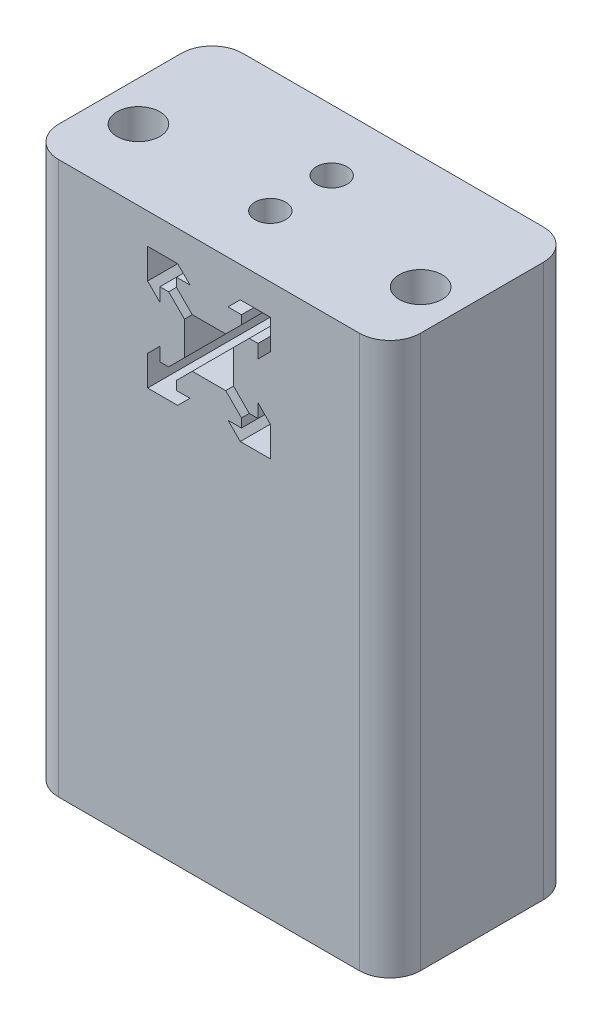
SolidWorks part; units mm, degrees
ref_plane "Front Plane" through (0, 0, 0) normal (0, 0, 1) x (1, 0, 0)
ref_plane "Top Plane" through (0, 0, 0) normal (0, 1, 0) x (1, 0, 0)
ref_plane "Right Plane" through (0, 0, 0) normal (1, 0, 0) x (0, 0, -1)
sketch "Sketch1" plane through (0, 0, 0) normal (0, 0, 1) x (1, 0, 0)
  line L1 (-29.5, 15) -> (29.5, 15)
  line L2 (-29.5, 15) -> (-29.5, -15)
  line L3 (-29.5, -15) -> (29.5, -15)
  line L4 (29.5, 15) -> (29.5, -15)
  line L5 (-29.5, 15) -> (29.5, -15) construction
  line L6 (-29.5, -15) -> (29.5, 15) construction
  line L90 (4, 2.7272) -> (6.5728, 5.3)
  line L91 (6.5728, 5.3) -> (8, 5.3)
  line L92 (8, 5.3) -> (8, 3.1)
  line L93 (8, 3.1) -> (10, 5.1)
  line L94 (10, 5.1) -> (10, 10)
  line L95 (10, 10) -> (5.1, 10)
  line L96 (5.1, 10) -> (3.1, 8)
  line L97 (3.1, 8) -> (5.3, 8)
  line L98 (5.3, 8) -> (5.3, 6.5728)
  line L99 (5.3, 6.5728) -> (2.7272, 4)
  line L100 (2.7272, 4) -> (-2.7272, 4)
  line L101 (-2.7272, 4) -> (-5.3, 6.5728)
  line L102 (-5.3, 6.5728) -> (-5.3, 8)
  line L103 (-5.3, 8) -> (-3.1, 8)
  line L104 (-3.1, 8) -> (-5.1, 10)
  line L105 (-5.1, 10) -> (-10, 10)
  line L106 (-10, 10) -> (-10, 5.1)
  line L107 (-10, 5.1) -> (-8, 3.1)
  line L108 (-8, 3.1) -> (-8, 5.3)
  line L109 (-8, 5.3) -> (-6.5728, 5.3)
  line L110 (-6.5728, 5.3) -> (-4, 2.7272)
  line L111 (-4, 2.7272) -> (-4, -2.7272)
  line L112 (-4, -2.7272) -> (-6.5728, -5.3)
  line L113 (-6.5728, -5.3) -> (-8, -5.3)
  line L114 (-8, -5.3) -> (-8, -3.1)
  line L115 (-8, -3.1) -> (-10, -5.1)
  line L116 (-10, -5.1) -> (-10, -10)
  line L117 (-10, -10) -> (-5.1, -10)
  line L118 (-5.1, -10) -> (-3.1, -8)
  line L119 (-3.1, -8) -> (-5.3, -8)
  line L120 (-5.3, -8) -> (-5.3, -6.5728)
  line L121 (-5.3, -6.5728) -> (-2.7272, -4)
  line L122 (-2.7272, -4) -> (2.7272, -4)
  line L123 (2.7272, -4) -> (5.3, -6.5728)
  line L124 (5.3, -6.5728) -> (5.3, -8)
  line L125 (5.3, -8) -> (3.1, -8)
  line L126 (3.1, -8) -> (5.1, -10)
  line L127 (5.1, -10) -> (10, -10)
  line L128 (10, -10) -> (10, -5.1)
  line L129 (10, -5.1) -> (8, -3.1)
  line L130 (8, -3.1) -> (8, -5.3)
  line L131 (8, -5.3) -> (6.5728, -5.3)
  line L132 (6.5728, -5.3) -> (4, -2.7272)
  line L133 (4, -2.7272) -> (4, 2.7272)
  point P2 (0, 0)
  dimension "D1" = 20
  dimension "D2" = 59
  dimension "D3" = 30
extrude "Boss-Extrude1" add sketch "Sketch1" against normal blind 30
sketch "Sketch2" plane through (0, 15, 0) normal (0, 1, 0) x (1, 0, 0)
  circle A0 centre (0, 10) radius 2.5
  circle A1 centre (0, 20) radius 2.5
  circle A7 centre (23, 11.5) radius 3.5
  circle A9 centre (-23, 11.5) radius 3.5
  dimension "D1" = 10
  dimension "D2" = 10
extrude "Cut-Extrude1" cut sketch "Sketch2" against normal through all
sketch "Sketch3" plane through (0, 0, 0) normal (0, 0, 1) x (1, 0, 0)
  line L5 (-29.5, -15) -> (29.5, -15)
  line L7 (-29.5, -15) -> (-29.5, -75)
  line L8 (29.5, -15) -> (29.5, -75)
  line L9 (-29.5, -75) -> (29.5, -75)
  dimension "D4" = 60
extrude "Boss-Extrude2" add sketch "Sketch3" against normal up to surface (30 mm away) up to face at (0, 0, -30)
fillet "Fillet1" radius 5 1 edges at (29.5, -30, 0)
fillet "Fillet2" radius 5 1 edges at (29.5, -30, -30)
fillet "Fillet3" radius 5 1 edges at (-29.5, -30, -30)
fillet "Fillet4" radius 5 1 edges at (-29.5, -30, 0)
sketch "Sketch4" plane through (0, 0, 0) normal (0, 1, 0) x (1, 0, 0)
  line L0 (-29.5, 15) -> (29.5, 15) construction
  line L1 (-29.5, 25) -> (-29.5, 5) construction
  line L2 (29.5, 25) -> (29.5, 5) construction
  circle A0 centre (-9.83, 15) radius 2.35
  circle A1 centre (9.84, 15) radius 2.3
  dimension "D3" = 4.7
  dimension "D4" = 4.6
  dimension "D1" = 19.67
  dimension "D2" = 19.67
